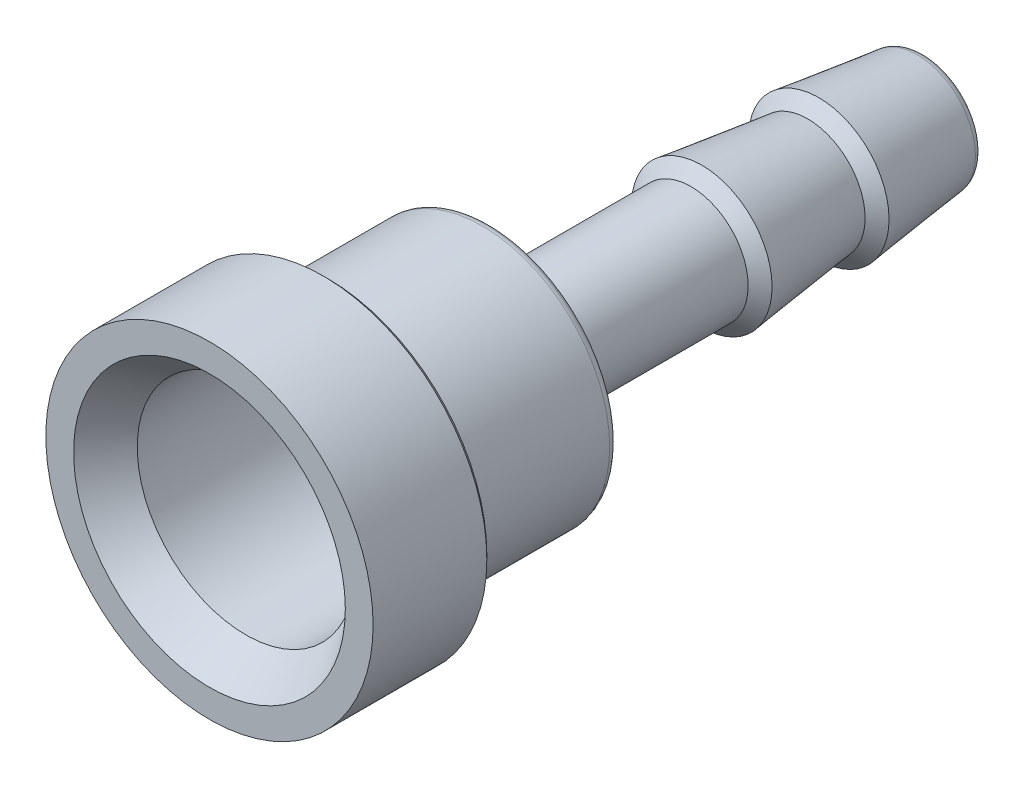
SolidWorks part; units mm, degrees
ref_plane "Front Plane" through (0, 0, 0) normal (0, 0, 1) x (1, 0, 0)
ref_plane "Top Plane" through (0, 0, 0) normal (0, 1, 0) x (1, 0, 0)
ref_plane "Right Plane" through (0, 0, 0) normal (1, 0, 0) x (0, 0, -1)
sketch "Sketch1" plane through (0, 0, 0) normal (1, 0, 0) x (0, 0, -1)
  line L0 (7.5415, 1.1112) -> (20.9296, 1.1112)
  line L1 (20.9296, 1.1112) -> (20.9296, 1.6764)
  line L2 (20.9296, 1.6764) -> (17.8266, 2.0574)
  line L3 (17.8266, 2.0574) -> (17.5069, 1.6764)
  line L4 (17.5069, 1.6764) -> (14.4039, 2.0574)
  line L5 (14.4039, 2.0574) -> (14.0842, 1.6764)
  line L6 (14.0842, 1.6764) -> (8.2296, 1.6764)
  line L7 (8.2296, 1.6764) -> (8.2296, 3.7338)
  line L8 (8.2296, 3.7338) -> (3.4544, 3.7338)
  line L9 (3.4544, 3.7338) -> (3.4544, 4.6609)
  line L10 (3.3274, 4.7879) -> (0, 4.7879)
  line L11 (0, 4.7879) -> (0, 3.9751)
  line L12 (0, 3.9751) -> (1.0618, 3.175)
  line L13 (9.4127, 0) -> (22.6727, 0) construction
  line L14 (7.5415, 1.1112) -> (6.35, 3.175)
  line L15 (6.35, 3.175) -> (1.0618, 3.175)
  line L16 (3.3274, 4.7879) -> (3.4544, 4.6609)
  dimension "D1" = 20.9296
  dimension "D2" = 3.4544
  dimension "D3" = 12.7
  dimension "D4" = 50
  dimension "D5" = 3.103
  dimension "D6" = 2.2225
  dimension "D7" = 3.3528
  dimension "D8" = 7.4676
  dimension "D9" = 9.5758
  dimension "D10" = 37
  dimension "D11" = 0.381
  dimension "D12" = 4.1148
  dimension "D13" = 7.9502
  dimension "D14" = 3.4227
  dimension "D15" = 4.7752
  dimension "D16" = 6.35
  dimension "D17" = 6.35
  dimension "D18" = 60
  dimension "D19" = 0.381
  dimension "D20" = 7
  dimension "D21" = 3.3528
  dimension "D22" = 45
  dimension "D23" = 0.127
revolve "Revolve1" add sketch "Sketch1" angle 360 about L13
fillet "Fillet1" [suppressed] radius 0.254
sketch "Sketch3" [suppressed] plane through (0, 0, 0) normal (1, 0, 0) x (0, 0, -1)
  line L0 (27.0256, 3.2512) -> (22.8092, 3.7689)
  line L1 (22.8092, 3.7689) -> (22.8092, 0)
  line L2 (0, 0) -> (33.9526, 0) construction
  line L3 (27.2796, -2.2225) -> (27.2796, 2.2225) construction
  line L4 (18.3388, 0) -> (18.3388, 3.7747)
  line L5 (18.3388, 3.7747) -> (22.8092, 3.2258)
  dimension "D1" = 83
  dimension "D2" = 22.8092
  dimension "D3" = 0.254
  dimension "D4" = 3.2512
  dimension "D5" = 18.3388
  dimension "D6" = 83
  dimension "D7" = 3.2258
fillet "Fillet2" radius 0.254 2 edges at (3.7338, 0, -8.2296) (1.6764, 0, -20.9296)
sketch "Sketch4" plane through (0, 0, 0) normal (1, 0, 0) x (0, 0, -1)
  line L0 (17.526, 2.0885) -> (20.6756, 1.7018)
  line L1 (20.9296, 0) -> (9.3832, 0) construction
  line L2 (17.526, 2.0885) -> (17.526, 1.6764)
  line L3 (17.526, 1.6764) -> (14.0716, 2.1005)
  line L4 (14.0716, 2.1005) -> (14.0716, 1.6764)
  line L5 (20.9296, -1.1112) -> (20.9296, 1.1112) construction
  line L6 (20.9296, 0) -> (20.9296, 3.8485)
  dimension "D1" = 1.7018
  dimension "D2" = 7
  dimension "D3" = 7
  dimension "D4" = 1.6764
  dimension "D5" = 3.4036
  dimension "D6" = 0.254
  dimension "D7" = 6.858
  dimension "D8" = 1.6764
